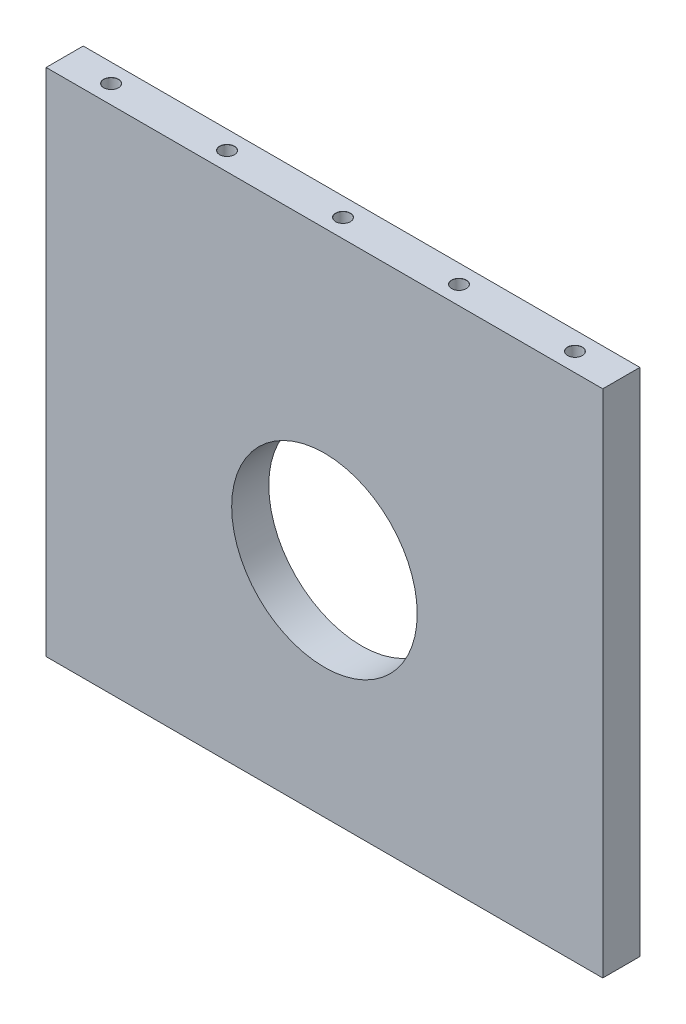
SolidWorks part; units mm, degrees
material "6061-T6 (SS)"
ref_plane "Front Plane" through (0, 0, 0) normal (0, 0, 1) x (1, 0, 0)
ref_plane "Top Plane" through (0, 0, 0) normal (0, 1, 0) x (1, 0, 0)
ref_plane "Right Plane" through (0, 0, 0) normal (1, 0, 0) x (0, 0, -1)
sketch "Sketch1" plane through (0, 0, 0) normal (0, 0, 1) x (1, 0, 0)
  line L1 (0, 0) -> (120, 0)
  line L2 (0, 0) -> (0, 110)
  line L3 (0, 110) -> (120, 110)
  line L4 (120, 0) -> (120, 110)
  dimension "D1" = 110
  dimension "D2" = 120
extrude "Boss-Extrude1" add sketch "Sketch1" along normal blind 8
sketch "Sketch2" plane through (0, 110, 0) normal (0, 1, 0) x (1, 0, 0)
  line L0 (0, -4) -> (120, -4) construction
  line L1 (0, -8) -> (0, 0) construction
  line L2 (120, -8) -> (120, 0) construction
  point P9 (60, -4)
  point P18 (85, -4)
  point P19 (110, -4)
  point P20 (60, -4)
  point P21 (85, -4)
  point P22 (35, -4)
  point P23 (60, -4)
  point P24 (35, -4)
  point P25 (10, -4)
  dimension "D1" = 3
  dimension "D2" = 3
hole_wizard "Tap Drill for M3 Helicoil1" positions "Sketch2" profile "Sketch4" hole size "M3x0.5" standard "DIN"
sketch "Sketch4" plane through (10, 110, 4) normal (1, 0, 0) x (0, 0, 1)
  line L0 (0, 0) -> (0, 6.9464)
  line L1 (0, 6.9464) -> (1.575, 6)
  line L2 (1.575, 6) -> (1.575, 0.025)
  line L3 (1.575, 0.025) -> (1.6, 0)
  line L5 (1.6, 0) -> (0, 0)
  line L6 (-1.575, 0.025) -> (-1.6, 0) construction
  line L10 (0, 6.9464) -> (-1.575, 6) construction
  line L11 (0, -6.35) -> (0, 107.95) construction
  dimension "Hole Dia." = 3.15
  dimension "Hole Depth" = 6
  dimension "Near C'Sink Dia." = 3.2
  dimension "Near C'Sink Angle" = 90
  dimension "Drill Angle" = 118
sketch "Sketch5" plane through (0, 0, 0) normal (0, 0, -1) x (-1, 0, 0)
  circle A2 centre (-60, 48) radius 10.5 construction
  circle A3 centre (-60, 48) radius 10.5
  point P4 (-60, 48)
hole_wizard "Ø40.0 (40) Diameter Hole1" positions "Sketch5" profile "Sketch7" hole size "Ø40.0" standard "DIN" end condition through all
sketch "Sketch7" plane through (60, 48, 0) normal (1, 0, 0) x (0, 1, 0)
  line L0 (0, 0) -> (0, 8)
  line L1 (0, 8) -> (20, 8)
  line L2 (20, 8) -> (20, 0)
  line L5 (20, 0) -> (0, 0)
  line L11 (0, -6.35) -> (0, 107.95) construction
  dimension "Thru Hole Dia." = 40
  dimension "Thru Hole Depth" = 8
